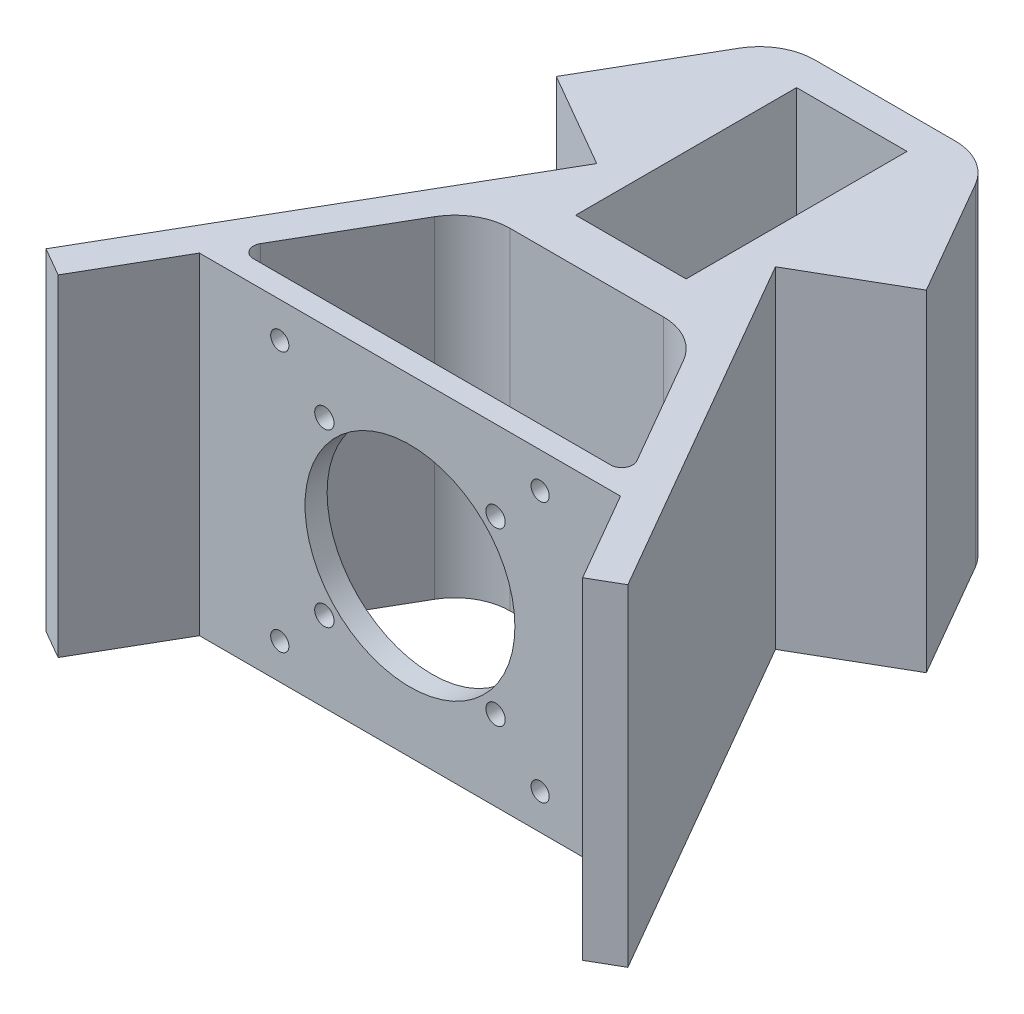
SolidWorks part; units mm, degrees
material "3.1355 (EN-AW 2024)"
ref_plane "Спереди" through (0, 0, 0) normal (0, 0, 1) x (1, 0, 0)
ref_plane "Сверху" through (0, 0, 0) normal (0, 1, 0) x (1, 0, 0)
ref_plane "Справа" through (0, 0, 0) normal (1, 0, 0) x (0, 0, -1)
sketch "Эскиз1" plane through (0, 0, 0) normal (0, 1, 0) x (1, 0, 0)
  line L12 (-38.1188, -50) -> (38.1188, -50)
  line L13 (38.1188, -50) -> (47.4833, -66.2199)
  line L14 (47.4833, -66.2199) -> (52.6795, -63.2199)
  line L15 (52.6795, -63.2199) -> (16.1795, 0)
  line L16 (16.1795, 0) -> (33.5, 10)
  line L17 (33.5, 10) -> (18.4889, 36)
  line L18 (18.4889, 36) -> (-18.4889, 36)
  line L19 (-18.4889, 36) -> (-33.5, 10)
  line L20 (-33.5, 10) -> (-16.1795, 0)
  line L21 (-16.1795, 0) -> (-52.6795, -63.2199)
  line L22 (-52.6795, -63.2199) -> (-47.4833, -66.2199)
  line L23 (-47.4833, -66.2199) -> (-38.1188, -50)
  line L24 (-35.8094, -46) -> (-19.6436, -18)
  line L25 (10, -10) -> (-10, -10)
  line L26 (10, -10) -> (10, 30)
  line L27 (10, 30) -> (-10, 30)
  line L28 (-10, -10) -> (-10, 30)
  line L29 (10, -10) -> (-10, 30) construction
  line L30 (10, 30) -> (-10, -10) construction
  line L31 (-19.6436, -18) -> (19.6436, -18)
  line L32 (19.6436, -18) -> (35.8094, -46)
  line L33 (35.8094, -46) -> (-35.8094, -46)
  point P11 (0, 36)
  point P13 (0, -50)
  point P14 (0, 10)
  point P24 (0, -18)
  point P25 (0, -46)
  dimension "D1" = 6
  dimension "D2" = 67
  dimension "D3" = 20
  dimension "D4" = 73
  dimension "D5" = 60
  dimension "D6" = 10
  dimension "D7" = 20
  dimension "D8" = 40
  dimension "D9" = 6
  dimension "D10" = 28
  dimension "D11" = 8
  dimension "D12" = 4
extrude "База" add sketch "Эскиз1" along normal mid plane 60
fillet "Скругление1" radius 10 4 edges at (19.6436, 0, 18) (-19.6436, 0, 18) (-18.4889, 0, -36) (18.4889, 0, -36)
fillet "Скругление2" radius 2 2 edges at (35.8094, 0, 46) (-35.8094, 0, 46)
sketch "Эскиз2" plane through (0, 0, 50) normal (0, 0, 1) x (1, 0, 0)
  line L0 (-15.5, -15.5) -> (-15.5, 0) construction
  line L1 (-15.5, 0) -> (-15.5, 15.5) construction
  line L2 (-15.5, -15.5) -> (0, -15.5) construction
  line L3 (0, -15.5) -> (15.5, -15.5) construction
  circle A0 centre (0, 0) radius 19
  circle A1 centre (-15.5, 15.5) radius 1.75
  circle A2 centre (15.5, 15.5) radius 1.75
  circle A3 centre (15.5, -15.5) radius 1.75
  circle A4 centre (-15.5, -15.5) radius 1.75
  dimension "D1" = 38
  dimension "D4" = 3.5
  dimension "D2" = 31
  dimension "D3" = 31
extrude "Nema17" cut sketch "Эскиз2" against normal up to next
hole_wizard "Nema23 - M4" positions "Эскиз3" profile "Эскиз4" tap size "M4" standard "ISO"
sketch "Эскиз3" plane through (0, 0, 50) normal (0, 0, 1) x (1, 0, 0)
  line L0 (-23.57, 23.57) -> (0, 23.57) construction
  line L1 (0, 23.57) -> (23.57, 23.57) construction
  line L2 (23.57, 23.57) -> (23.57, 0) construction
  line L3 (23.57, 0) -> (23.57, -23.57) construction
  point P0 (-23.57, 23.57)
  point P2 (23.57, 23.57)
  point P4 (23.57, -23.57)
  point P6 (-23.57, -23.57)
  dimension "D1" = 47.14
  dimension "D2" = 47.14
sketch "Эскиз4" plane through (-23.57, 23.57, 50) normal (1, 0, 0) x (0, -1, 0)
  line L0 (0, 0) -> (0, 4.9904)
  line L1 (0, 4.9904) -> (1.65, 3.999)
  line L2 (1.65, 3.999) -> (1.65, 0)
  line L5 (1.65, 0) -> (0, 0)
  line L10 (0, 4.9904) -> (-1.65, 3.999) construction
  line L11 (0, -6.35) -> (0, 107.95) construction
  dimension "Диаметр сверла" = 3.3
  dimension "Глубина сверла" = 3.999
  dimension "Угол заточки сверла" = 118
cosmetic thread "Отверстие резьбы1" parameters "D1"=4, "D2"=4
cosmetic thread "Отверстие резьбы2" parameters "D1"=4, "D2"=4
cosmetic thread "Отверстие резьбы3" parameters "D1"=4, "D2"=4
cosmetic thread "Отверстие резьбы4" parameters "D1"=4, "D2"=4
